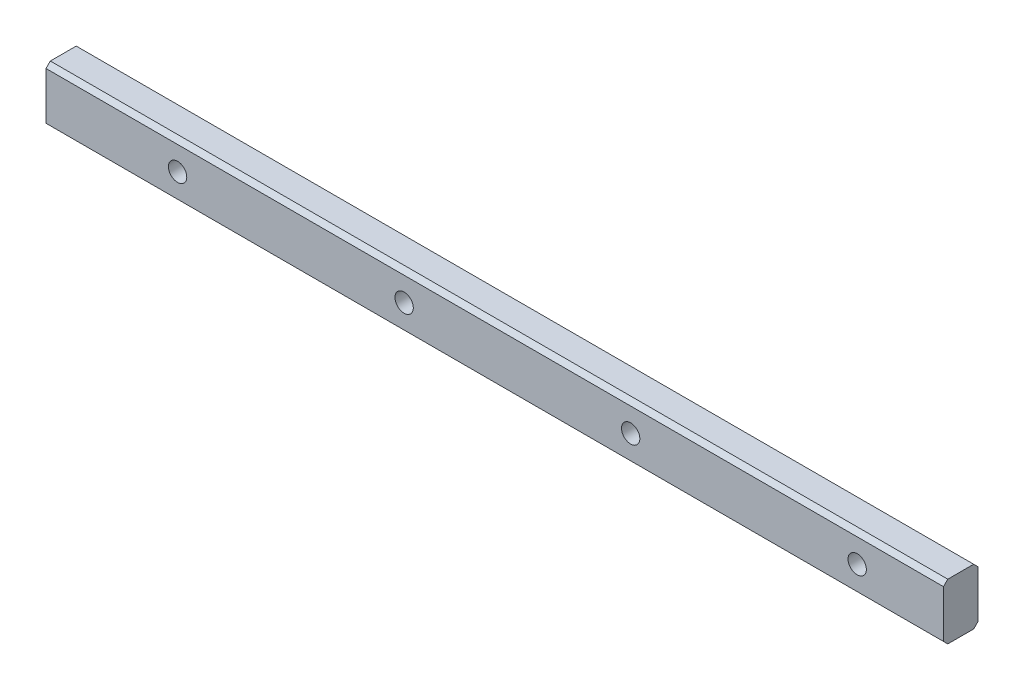
SolidWorks part; units mm, degrees
material "45"
ref_plane "基准面1" through (0, 0, 0) normal (0, 0, 1) x (1, 0, 0)
ref_plane "基准面2" through (0, 0, 0) normal (0, 1, 0) x (1, 0, 0)
ref_plane "基准面3" through (0, 0, 0) normal (1, 0, 0) x (0, 0, -1)
sketch "尺寸草图" plane through (0, 0, 0) normal (0, 0, 1) x (1, 0, 0)
  line L0 (-208, 0) -> (208, 0) construction
  point P3 (-16, 0)
  point P4 (-0.8, 0)
  point P5 (0, 0)
  point P8 (-28, 0)
  point P11 (0, 0)
  dimension "L" = 416
  dimension "b" = 28
  dimension "h" = 16
  dimension "C" = 0.8
  dimension "r" = 0.8
sketch "草图1" plane through (0, 0, 0) normal (0, 0, 1) x (1, 0, 0)
  line L0 (-28.0599, 0) -> (30.562, 0) construction
  line L1 (-208, 14) -> (208, 14)
  line L2 (-208, -14) -> (208, -14)
  line L3 (0, 2.9108) -> (0, -2.1805) construction
  line L4 (-208, 14) -> (-208, -14)
  line L5 (208, 14) -> (208, -14)
  dimension "D3" = 416
  dimension "D1" = 14
extrude "基体-拉伸" add sketch "草图1" along normal blind 16
fillet "圆角1" radius 0.8 4 edges at (0, -14, 16) (0, -14, 0) (0, 14, 0) (0, 14, 16)
sketch "草图2" plane through (-208, 0, 0) normal (-1, 0, 0) x (0, 0, 1)
  line L0 (16, 13) -> (0, 13)
  line L1 (16, 13.2) -> (16, -13.2) construction
  line L2 (0, 13.2) -> (0, -13.2) construction
  line L3 (16, -13) -> (0, -13)
  line L9 (16, 13) -> (16, 13.2)
  line L10 (0, -13) -> (0, -13.2)
  line L13 (16, -13.2) -> (16, 13.2)
  line L14 (15.2, 14) -> (0.8, 14)
  line L15 (0, 13.2) -> (0, -13.2)
  line L16 (0.8, -14) -> (15.2, -14)
  line L17 (16, -13.2) -> (16, -13)
  line L18 (15.2, 14) -> (0.8, 14)
  line L19 (0, 13.2) -> (0, 13)
  line L20 (0.8, -14) -> (15.2, -14)
  arc A8 (16, 13.2) -> (15.2, 14) centre (15.2, 13.2) ccw
  arc A9 (0.8, 14) -> (0, 13.2) centre (0.8, 13.2) ccw
  arc A10 (0, -13.2) -> (0.8, -14) centre (0.8, -13.2) ccw
  arc A11 (15.2, -14) -> (16, -13.2) centre (15.2, -13.2) ccw
  arc A12 (16, 13.2) -> (15.2, 14) centre (15.2, 13.2) ccw
  arc A13 (0.8, 14) -> (0, 13.2) centre (0.8, 13.2) ccw
  arc A14 (0, -13.2) -> (0.8, -14) centre (0.8, -13.2) ccw
  arc A15 (15.2, -14) -> (16, -13.2) centre (15.2, -13.2) ccw
  dimension "D2" = 1
  dimension "D3" = 1
  dimension "D1" = 0
extrude "切除-拉伸1" cut sketch "草图2" against normal through all
chamfer "倒角1" distance 2 angle 45 4 edges at (0, -13, 0) (0, 13, 0) (0, -13, 16) (0, 13, 16)
hole_wizard "M10 螺纹孔1" positions "草图3" profile "草图4" tap size "M10" standard "GB" end condition through all
sketch "草图3" plane through (0, 0, 16) normal (0, 0, 1) x (1, 0, 0)
  line L0 (208, -11) -> (208, 11) construction
  line L1 (-208, 13) -> (208, 13) construction
  point P0 (-147, 0)
  point P2 (-42, 0)
  point P4 (63, 0)
  point P6 (168, 0)
  point P13 (0, 0)
  dimension "D1" = 40
  dimension "D2" = 105
  dimension "D3" = 105
  dimension "D4" = 105
  dimension "D5" = 13
sketch "草图4" plane through (-147, 0, 16) normal (1, 0, 0) x (0, -1, 0)
  line L0 (0, 0) -> (0, 16)
  line L1 (0, 16) -> (4.25, 16)
  line L2 (4.25, 16) -> (4.25, 0)
  line L5 (4.25, 0) -> (0, 0)
  line L11 (0, -6.35) -> (0, 107.95) construction
  dimension "通孔螺纹孔钻头直径" = 8.5
  dimension "通孔螺纹孔钻头深度" = 16
cosmetic thread "孔螺蚊线1" parameters "D2"=10
cosmetic thread "孔螺蚊线2" parameters "D2"=10
cosmetic thread "孔螺蚊线3" parameters "D2"=10
cosmetic thread "孔螺蚊线4" parameters "D2"=10
equation "\"D3@草图1\" = \"L@尺寸草图\""
equation "\"D1@草图1\" = \"b@尺寸草图\" / 2"
equation "\"D1@圆角1\" = \"r@尺寸草图\""
equation "\"D1@基体-拉伸\" = \"h@尺寸草图\""
